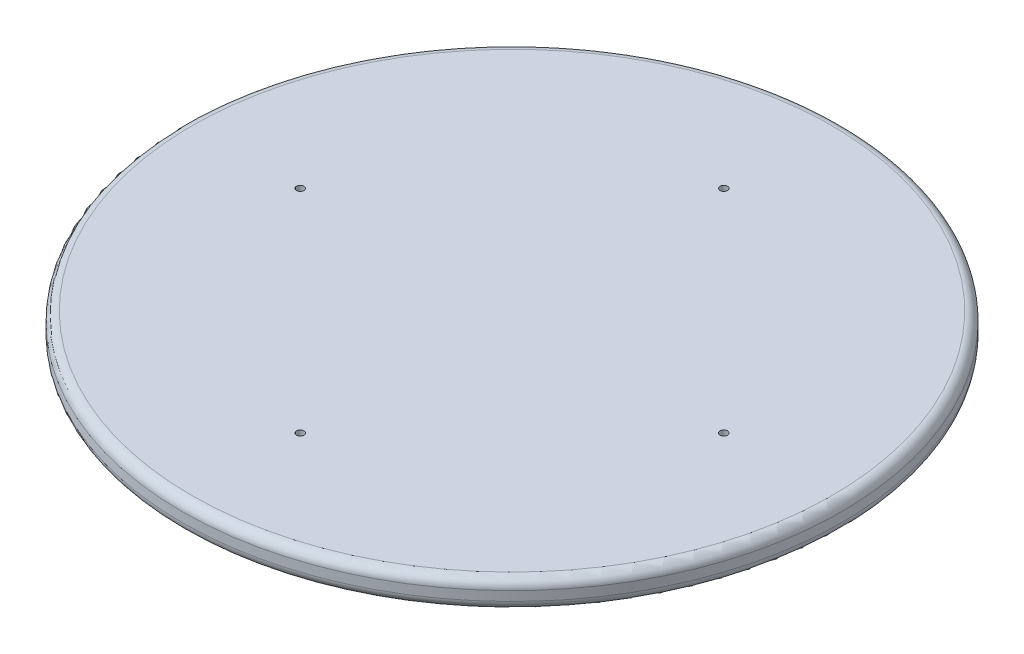
SolidWorks part; units mm, degrees
material "Pine"
ref_plane "Front Plane" through (0, 0, 0) normal (0, 0, 1) x (1, 0, 0)
ref_plane "Top Plane" through (0, 0, 0) normal (0, 1, 0) x (1, 0, 0)
ref_plane "Right Plane" through (0, 0, 0) normal (1, 0, 0) x (0, 0, -1)
sketch "Sketch1" plane through (0, 0, 0) normal (0, 1, 0) x (1, 0, 0)
  circle A0 centre (0, 0) radius 350
  dimension "D1" = 700
extrude "Boss-Extrude1" add sketch "Sketch1" along normal blind 30
fillet "Fillet1" radius 10 2 edges at (0, 0, 350) (0, 30, 350)
sketch "Sketch2" plane through (0, 30, 0) normal (0, 1, 0) x (1, 0, 0)
  line L0 (0, 0) -> (0, 340) construction
  line L1 (0, 0) -> (0, -340) construction
  line L2 (0, 0) -> (340, 0) construction
  line L3 (0, 0) -> (-340, 0) construction
  circle A0 centre (0, 0) radius 340 construction
  circle A5 centre (0, 225) radius 4
  circle A6 centre (225, 0) radius 4
  circle A7 centre (0, -225) radius 4
  circle A8 centre (-225, 0) radius 4
  point P20 (0, 0)
  dimension "D1" = 225
  dimension "D2" = 8
  dimension "D3" = 4
extrude "Cut-Extrude1" cut sketch "Sketch2" against normal mid plane 96
